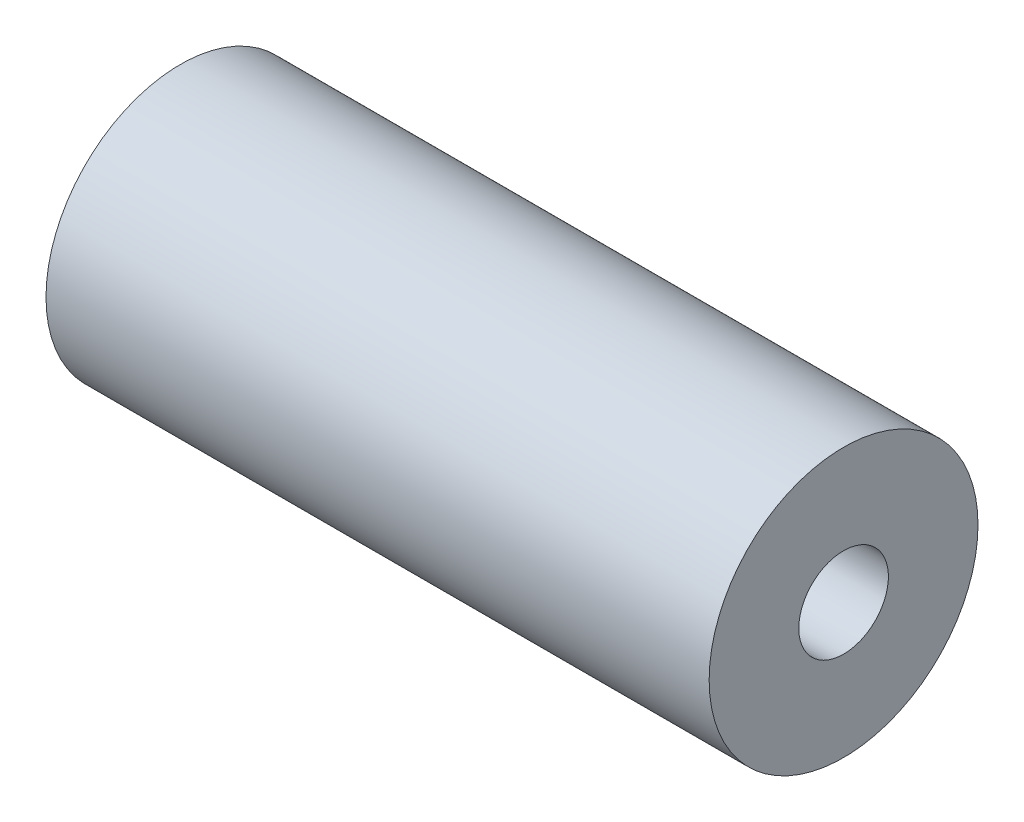
SolidWorks part; units mm, degrees
material "PTFE (general)"
ref_plane "Front Plane" through (0, 0, 0) normal (0, 0, 1) x (1, 0, 0)
ref_plane "Top Plane" through (0, 0, 0) normal (0, 1, 0) x (1, 0, 0)
ref_plane "Right Plane" through (0, 0, 0) normal (1, 0, 0) x (0, 0, -1)
sketch "Axial profile (mm)" plane through (0, 0, 0) normal (0, 0, 1) x (1, 0, 0)
  line L0 (-110, 0) -> (75, 0) construction
  line L1 (-140, 2.5) -> (-103, 2.5)
  line L2 (-103, 2.5) -> (-103, 7.5)
  line L3 (-103, 7.5) -> (-140, 7.5)
  line L4 (-140, 7.5) -> (-140, 2.5)
revolve "Full revolution" add sketch "Axial profile (mm)" angle 360 about L0
